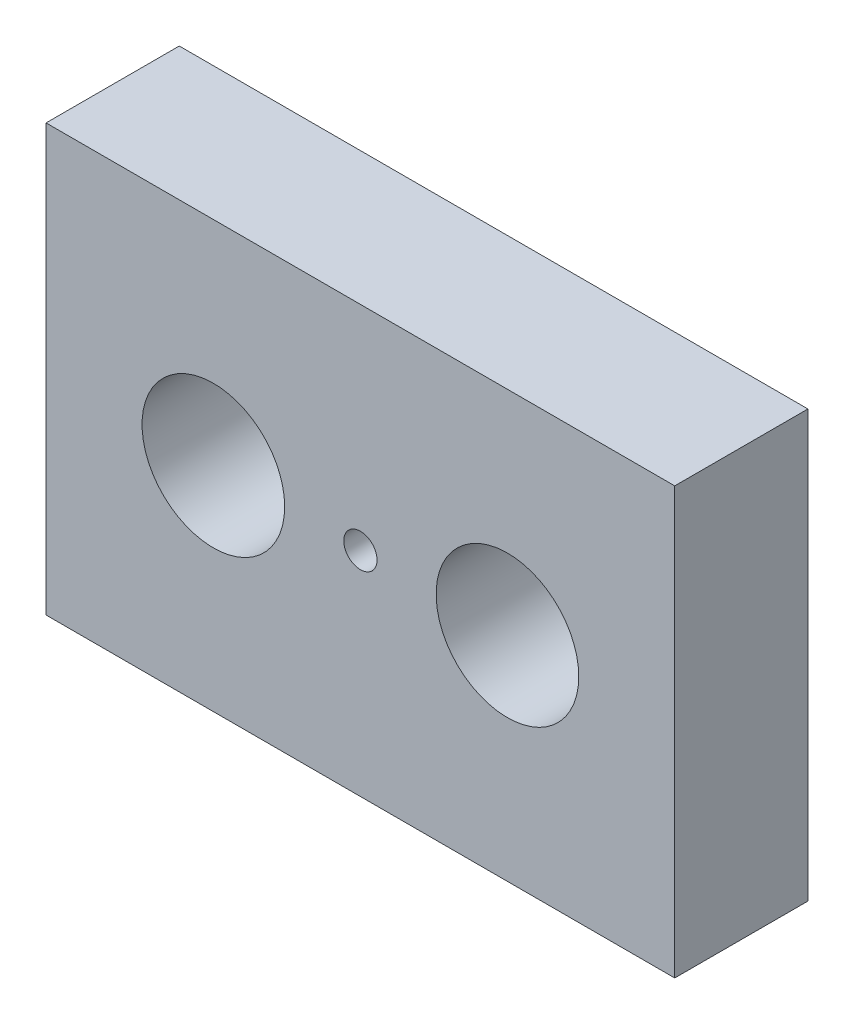
SolidWorks part; units mm, degrees
material "Balsa"
ref_plane "Front Plane" through (0, 0, 0) normal (0, 0, 1) x (1, 0, 0)
ref_plane "Top Plane" through (0, 0, 0) normal (0, 1, 0) x (1, 0, 0)
ref_plane "Right Plane" through (0, 0, 0) normal (1, 0, 0) x (0, 0, -1)
sketch "Sketch1" plane through (0, 0, 0) normal (0, 0, 1) x (1, 0, 0)
  line L1 (0, 0) -> (14.986, 0)
  line L2 (0, 0) -> (0, 10.16)
  line L3 (0, 10.16) -> (14.986, 10.16)
  line L4 (14.986, 0) -> (14.986, 10.16)
  dimension "D1" = 14.986
  dimension "D2" = 10.16
extrude "Boss-Extrude1" add sketch "Sketch1" along normal blind 3.175
hole_wizard "M3 Clearance Hole1" positions "Sketch3" profile "Sketch2" hole size "M3" standard "Ansi Metric"
sketch "Sketch3" plane through (0, 0, 3.175) normal (0, 0, 1) x (1, 0, 0)
  line L0 (3.9878, 5.08) -> (0, 5.08) construction
  line L1 (0, 10.16) -> (0, 0) construction
  line L3 (10.9982, 5.08) -> (14.986, 5.08) construction
  line L4 (14.986, 0) -> (14.986, 10.16) construction
  point P0 (10.9982, 5.08)
  point P1 (3.9878, 5.08)
  dimension "D1" = 7.0104
sketch "Sketch2" plane through (10.9982, 5.08, 3.175) normal (1, 0, 0) x (0, -1, 0)
  line L0 (0, 0) -> (0, 11.0215)
  line L1 (0, 11.0215) -> (1.7, 10)
  line L2 (1.7, 10) -> (1.7, 0)
  line L5 (1.7, 0) -> (0, 0)
  line L10 (0, 11.0215) -> (-1.7, 10) construction
  line L11 (0, -6.35) -> (0, 107.95) construction
  dimension "Hole Dia." = 3.4
  dimension "Hole Depth" = 10
  dimension "Drill Angle" = 118
sketch "Sketch4" plane through (0, 0, 3.175) normal (0, 0, 1) x (1, 0, 0)
  line L0 (3.9878, 5.08) -> (10.9982, 5.08) construction
  circle A0 centre (7.493, 5.08) radius 0.3969
  dimension "D1" = 0.7937
extrude "Cut-Extrude1" cut sketch "Sketch4" against normal through all
